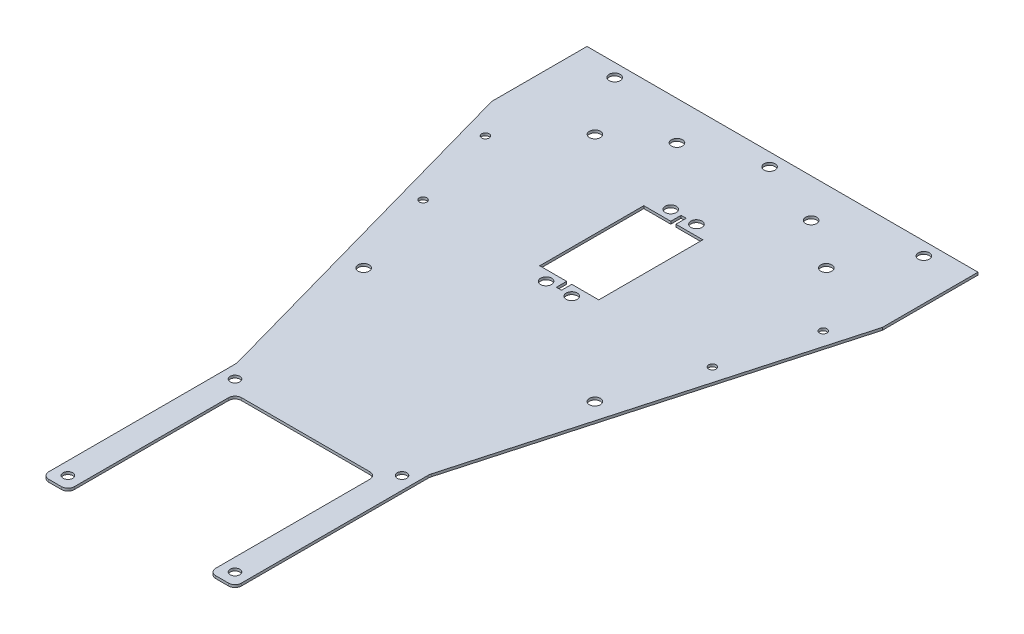
SolidWorks part; units mm, degrees
ref_plane "Front Plane" through (0, 0, 0) normal (0, 0, 1) x (1, 0, 0)
ref_plane "Top Plane" through (0, 0, 0) normal (0, 1, 0) x (1, 0, 0)
ref_plane "Right Plane" through (0, 0, 0) normal (1, 0, 0) x (0, 0, -1)
sketch "Sketch26" plane through (0, 0, 0) normal (0, 1, 0) x (1, 0, 0)
  line L0 (76.0133, 88.8235) -> (76.0133, 51.6238)
  line L1 (76.0133, 88.8235) -> (-76.1021, 88.8235)
  line L2 (37.6734, -85.3501) -> (75.5021, 49.7977)
  line L3 (45.09, 63.6995) -> (45.09, 54.4377) construction
  line L4 (76.0133, 51.6238) -> (63.6788, 55.0763) construction
  line L5 (29.9883, -161.7164) -> (34.9883, -161.7164)
  line L6 (76.0133, 51.6238) -> (75.5021, 49.7977)
  line L7 (27.4883, -159.2164) -> (27.4883, -99.2164)
  line L8 (11.5777, 5.7174) -> (11.5777, 46.2174)
  line L9 (1.09, 1.7174) -> (-0.91, 1.7174)
  line L10 (-11.3978, 5.7174) -> (-11.3978, 46.2174)
  line L11 (1.09, 5.7174) -> (11.5777, 5.7174)
  line L12 (0, 119.0602) -> (0, 33.226) construction
  line L15 (-44.91, -22.0666) -> (-44.91, -53.7446) construction
  line L18 (1.09, 50.2174) -> (-0.91, 50.2174)
  line L21 (45.09, -22.0755) -> (45.09, -53.7446) construction
  line L24 (-44.91, 63.6995) -> (-44.91, 54.4377) construction
  line L28 (-76.1021, 51.7763) -> (-76.1021, 88.8235)
  line L29 (1.09, 46.2174) -> (11.5777, 46.2174)
  line L31 (-37.5, -159.2164) -> (-37.5, -86.6615)
  line L33 (-0.91, 1.7174) -> (-0.91, 5.7174)
  line L34 (-0.91, 50.2174) -> (-0.91, 46.2174)
  line L36 (1.09, 50.2174) -> (1.09, 46.2174)
  line L37 (-0.91, 46.2174) -> (-11.3978, 46.2174)
  line L38 (1.09, 1.7174) -> (1.09, 5.7174)
  line L50 (-0.91, 5.7174) -> (-11.3978, 5.7174)
  line L51 (-27.5, -159.2169) -> (-27.4883, -99.216)
  line L53 (-30, -161.7164) -> (-35, -161.7164)
  line L54 (-37.6855, -85.3123) -> (-76.1021, 51.7763)
  line L55 (-24.9883, -96.7164) -> (24.9883, -96.7164)
  line L69 (37.4883, -159.2164) -> (37.4883, -86.6979)
  circle A0 centre (45.09, 60.7174) radius 2.15
  circle A1 centre (45.09, -29.2826) radius 2.15
  circle A2 centre (5.09, 50.2174) radius 2.15
  circle A3 centre (5.09, 1.7174) radius 2.15
  circle A4 centre (-26.1021, 73.8235) radius 2.15
  circle A5 centre (0, 83.748) radius 2.15
  circle A6 centre (26.1021, 73.8235) radius 2.15
  circle A10 centre (60, 83.7476) radius 2.15
  circle A11 centre (-32.5, -91.7164) radius 1.875
  circle A12 centre (-32.5, -156.7164) radius 1.875
  circle A14 centre (-56.2751, 5.2271) radius 1.45
  circle A15 centre (5.09, 50.2174) radius 2.15
  circle A16 centre (-65.7103, 38.9314) radius 1.45
  circle A17 centre (-4.91, 50.2174) radius 2.15
  circle A18 centre (-60.2633, 83.7476) radius 2.15
  arc A23 (37.6734, -85.3501) -> (37.4883, -86.6979) centre (42.4883, -86.6979) ccw
  circle A25 centre (-4.91, 1.7174) radius 2.15
  circle A26 centre (-4.91, 50.2174) radius 2.15
  circle A27 centre (-44.91, -29.2826) radius 2.15
  circle A28 centre (-44.91, 60.7174) radius 2.15
  arc A29 (37.4883, -159.2164) -> (34.9883, -161.7164) centre (34.9883, -159.2164) cw
  arc A30 (29.9883, -161.7164) -> (27.4883, -159.2164) centre (29.9883, -159.2164) cw
  arc A31 (27.4883, -99.2164) -> (24.9883, -96.7164) centre (24.9883, -99.2164) ccw
  arc A32 (-24.9883, -96.7164) -> (-27.4883, -99.216) centre (-24.9883, -99.2164) ccw
  arc A33 (-27.5, -159.2169) -> (-30, -161.7164) centre (-30, -159.2164) cw
  arc A34 (-35, -161.7164) -> (-37.5, -159.2164) centre (-35, -159.2164) cw
  arc A35 (-37.6855, -85.3123) -> (-37.5, -86.6615) centre (-42.5, -86.6615) cw
  circle A50 centre (65.7107, 38.9311) radius 1.45
  circle A51 centre (56.2765, 5.2265) radius 1.45
  circle A57 centre (32.4883, -156.7164) radius 1.875
  circle A60 centre (32.4883, -91.7164) radius 1.875
  point P38 (0, 88.8235)
  point P42 (0.09, 1.7174)
  point P48 (0, 78.8235)
  point P99 (-0.285, 50.2174)
  point P100 (0, -96.7164)
  point P107 (0.09, 1.7174)
  point P111 (0, 78.8235)
  point P119 (-0.0444, 88.8235)
  point P122 (0.09, 50.2174)
  point P126 (-0.0444, 88.8235)
  point P127 (0, 78.8235)
  point P128 (0.4649, 50.2174)
  point P137 (27.4883, -96.7164)
  dimension "D6" = 4.3
  dimension "D13" = 15
  dimension "D10" = 4.3
  dimension "D7" = 50
  dimension "D8" = 4.3
  dimension "D22" = 10.5
  dimension "D4" = 48.5
  dimension "D11" = 4.3
  dimension "D36" = 65
  dimension "D37" = 5
  dimension "D38" = 2.9
  dimension "D41" = 2.9
  dimension "D47" = 3.75
  dimension "D54" = 60
  dimension "D33" = 4.3
  dimension "D51" = 4.3
  dimension "D53" = 4.3
  dimension "D9" = 5
  dimension "D23" = 5
  dimension "D5" = 5
  dimension "D12" = 5.0759
  dimension "D25" = 4
  dimension "D29" = 5
  dimension "D30" = 31
  dimension "D32" = 4
  dimension "D34" = 15
  dimension "D35" = 5
  dimension "D42" = 35
  dimension "D44" = 40
  dimension "D48" = 5
  dimension "D49" = 6.5
  dimension "D50" = 6.5
extrude "Boss-Extrude6" add sketch "Sketch26" along normal blind 1
